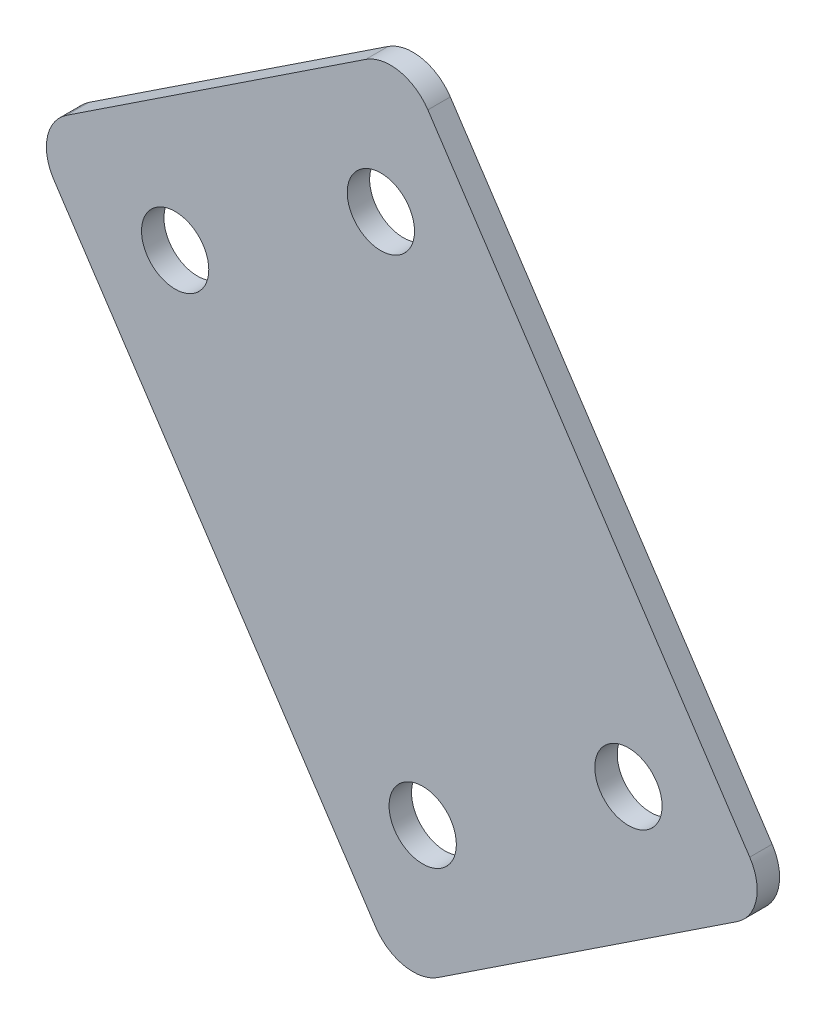
SolidWorks part; units mm, degrees
material "A-玻璃纤维"
ref_plane "前视基准面" through (0, 0, 0) normal (0, 0, 1) x (1, 0, 0)
ref_plane "上视基准面" through (0, 0, 0) normal (0, 1, 0) x (1, 0, 0)
ref_plane "右视基准面" through (0, 0, 0) normal (1, 0, 0) x (0, 0, -1)
other "Configuration Table"
sketch "草图1" plane through (0, 0, 0) normal (0, 0, 1) x (1, 0, 0)
  line L0 (15.514, -5.3211) -> (1.1637, 16.3599)
  line L1 (-1.608, 16.9238) -> (-14.9501, 8.0928)
  line L2 (-15.514, 5.3211) -> (-1.1637, -16.3599)
  line L3 (1.608, -16.9238) -> (14.9501, -8.0928)
  arc A0 (14.9501, -8.0928) -> (15.514, -5.3211) centre (13.8463, -6.425) ccw
  arc A1 (1.1637, 16.3599) -> (-1.608, 16.9238) centre (-0.5041, 15.256) ccw
  arc A2 (-14.9501, 8.0928) -> (-15.514, 5.3211) centre (-13.8463, 6.425) ccw
  arc A3 (-1.1637, -16.3599) -> (1.608, -16.9238) centre (0.5041, -15.256) ccw
  arc A4 (11.3566, -4.4753) -> (8.8549, -6.1311) centre (10.1057, -5.3032) ccw
  arc A5 (8.8549, -6.1311) -> (11.3566, -4.4753) centre (10.1057, -5.3032) ccw
  arc A6 (2.1838, -10.5466) -> (-0.3178, -12.2024) centre (0.933, -11.3745) ccw
  arc A7 (-0.3178, -12.2024) -> (2.1838, -10.5466) centre (0.933, -11.3745) ccw
  arc A8 (-8.8549, 6.1311) -> (-11.3566, 4.4753) centre (-10.1057, 5.3032) ccw
  arc A9 (-11.3566, 4.4753) -> (-8.8549, 6.1311) centre (-10.1057, 5.3032) ccw
  arc A10 (0.3178, 12.2024) -> (-2.1838, 10.5466) centre (-0.933, 11.3745) ccw
  arc A11 (-2.1838, 10.5466) -> (0.3178, 12.2024) centre (-0.933, 11.3745) ccw
extrude "凸台-拉伸1" add sketch "草图1" along normal blind 1
